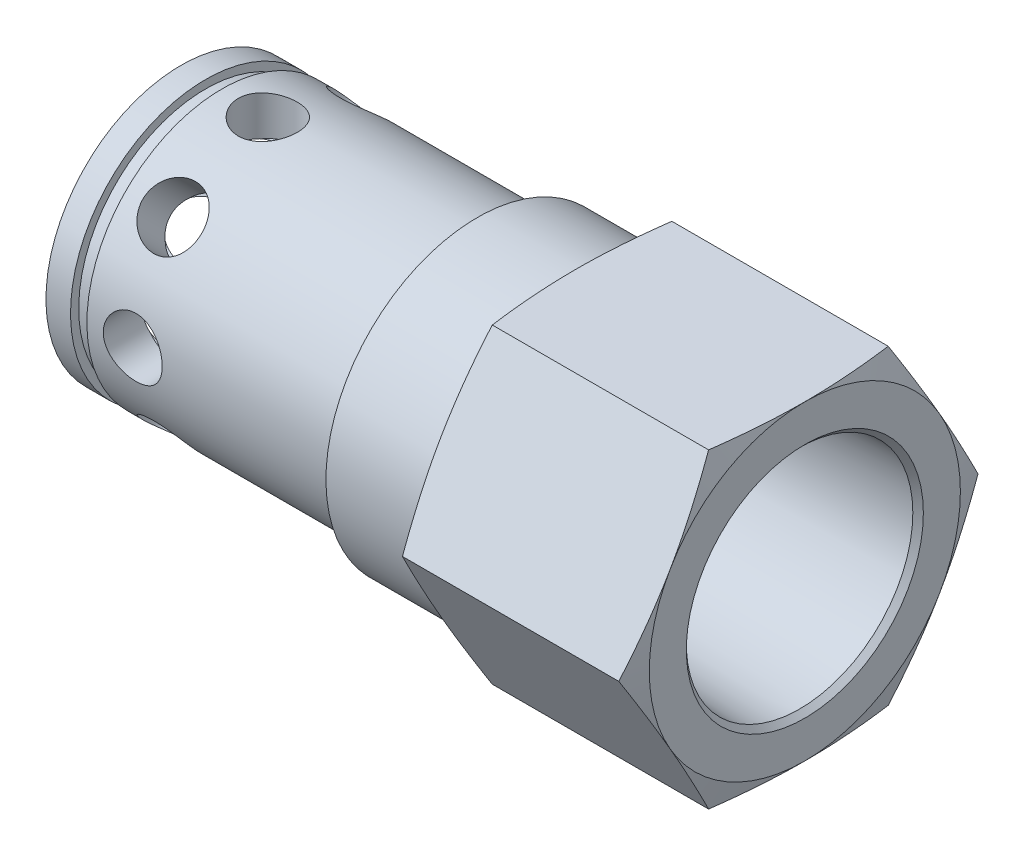
SolidWorks part; units mm, degrees
material "AISI 316 Annealed Stainless Steel Bar (SS)"
ref_plane "Front Plane" through (0, 0, 0) normal (0, 0, 1) x (1, 0, 0)
ref_plane "Top Plane" through (0, 0, 0) normal (0, 1, 0) x (1, 0, 0)
ref_plane "Right Plane" through (0, 0, 0) normal (1, 0, 0) x (0, 0, -1)
sketch "Sketch1" plane through (0, 0, 0) normal (1, 0, 0) x (0, 0, -1)
  line L1 (10.9697, 0) -> (5.4848, 9.5)
  line L2 (5.4848, 9.5) -> (-5.4848, 9.5)
  line L3 (-5.4848, 9.5) -> (-10.9697, 0)
  line L4 (-10.9697, 0) -> (-5.4848, -9.5)
  line L5 (-5.4848, -9.5) -> (5.4848, -9.5)
  line L6 (5.4848, -9.5) -> (10.9697, 0)
  circle A0 centre (0, 0) radius 9.5 construction
  circle A1 centre (0, 0) radius 3
  dimension "D2" = 6
  dimension "D1" = 19
extrude "Boss-Extrude1" add sketch "Sketch1" along normal blind 38.1
sketch "Sketch2" plane through (0, 0, 0) normal (0, 0, 1) x (1, 0, 0)
  line L0 (0, 0) -> (38.1, 0) construction
  line L1 (38.1, 0) -> (0, 0) construction
  line L2 (38.1, 0) -> (38.1, -9.5) construction
  line L3 (38.1, 9.5) -> (0, 9.5) construction
  line L4 (24.1, 9.5) -> (24.1, 9.25)
  line L5 (24.1, 9.25) -> (18.1, 9.25)
  line L6 (18.1, 9.25) -> (18.1, 8.25)
  line L7 (18.1, 8.25) -> (2.5, 8.25)
  line L8 (0, 9.5) -> (0, 0) construction
  line L9 (1.5, 8.25) -> (0, 8.25)
  line L10 (24.1, 9.5) -> (25.0378, 13)
  line L11 (1.5, 8.25) -> (1.5, 7.75)
  line L12 (1.5, 7.75) -> (2.5, 7.75)
  line L13 (2.5, 8.25) -> (2.5, 7.75)
  line L14 (25.0378, 13) -> (0, 13)
  line L15 (0, 13) -> (0, 8.25)
  line L16 (38.1, 9.5) -> (38.1, 13)
  line L17 (38.1, 13) -> (37.1622, 13)
  line L18 (37.1622, 13) -> (38.1, 9.5)
  dimension "D1" = 8.25
  dimension "D2" = 7.75
  dimension "D3" = 1.5
  dimension "D4" = 2.5
  dimension "D5" = 9.25
  dimension "D6" = 24.1
  dimension "D7" = 6
  dimension "D8" = 15
  dimension "D9" = 13
  dimension "D10" = 15
revolve "Cut-Revolve1" cut sketch "Sketch2" angle 360 about L0
sketch "Sketch3" plane through (0, 0, 0) normal (0, 0, 1) x (1, 0, 0)
  line L0 (0, 5.85) -> (9.9, 5.85)
  line L1 (0, 8.25) -> (0, -8.25) construction
  line L2 (9.9, 5.85) -> (10.95, 4.8)
  line L3 (10.95, 4.8) -> (13, 4.8)
  line L4 (13, 4.8) -> (13, 6.25)
  line L5 (13, 6.25) -> (15.5, 6.25)
  line L6 (15.5, 6.25) -> (15.5, 4.8)
  line L7 (15.5, 4.8) -> (21.4, 4.8)
  line L8 (21.4, 4.8) -> (21.4, 0)
  line L9 (0, 0) -> (21.4, 0)
  line L10 (0, 0) -> (0, 5.85)
  dimension "D1" = 9.9
  dimension "D2" = 21.4
  dimension "D3" = 13
  dimension "D4" = 2.5
  dimension "D5" = 4.8
  dimension "D6" = 5.85
  dimension "D7" = 45
  dimension "D8" = 6.25
revolve "Cut-Revolve2" cut sketch "Sketch3" angle 360 about L9
fillet "Fillet1" radius 0.2 2 edges at (15.5, 0, 6.25) (13, 0, 6.25)
hole_wizard "1/4 NPT Tapped Hole1" positions "Sketch5" profile "Sketch4" size "1/4" standard "ANSI Inch"
sketch "Sketch5" plane through (38.1, 0, 0) normal (1, 0, 0) x (0, 0, -1)
  point P0 (0, 0)
sketch "Sketch4" plane through (38.1, 0, 0) normal (0, 1, 0) x (0, 0, -1)
  line L0 (0, 0) -> (0, 14.2)
  line L1 (5.5626, 14.2) -> (0, 14.2)
  line L2 (-5.5626, 14.2) -> (0, 14.2) construction
  line L3 (5.5626, 14.2) -> (5.5626, 12)
  line L4 (5.5626, 12) -> (6.5676, 12)
  line L5 (6.5676, 12) -> (6.9173, 0.3217)
  line L6 (6.9173, 0.3217) -> (7.239, 0)
  line L7 (7.239, 0) -> (0, 0)
  line L8 (0, -6.35) -> (0, 107.95) construction
  line L9 (-6.9173, 0.3217) -> (-7.239, 0) construction
  line L11 (-5.5626, 12) -> (-6.5676, 12) construction
  line L12 (-6.5676, 12) -> (-6.9173, 0.3217) construction
  dimension "Tap Drill Dia." = 11.1252
  dimension "Tap Drill Depth" = 14.2
  dimension "Thread Dia." = 13.8345
  dimension "Thread Angle" = 3.43
  dimension "Thread Depth" = 12
  dimension "C'Sink Dia." = 14.478
  dimension "C'Sink Angle" = 90
  dimension "Drill Angle" = 180
ref_plane "Plane1" through (0, 0, 8.25) normal (0, 0, 1) x (1, 0, 0)
sketch "Sketch12" plane through (0, 0, 0) normal (0, 1, 0) x (1, 0, 0)
  line L0 (5.3, 8.25) -> (5.3, 5.6298)
  line L1 (18.1, 8.25) -> (2.5, 8.25) construction
  line L2 (5.3, 8.25) -> (7.1, 8.25)
  line L3 (7.1, 8.25) -> (7.1, 5.75)
  line L4 (7.1, 5.75) -> (6.9, 5.6298)
  line L5 (6.9, 5.6298) -> (5.3, 5.6298)
  line L6 (0, 8.25) -> (0, -8.25) construction
  dimension "D1" = 1.8
  dimension "D2" = 2.5
  dimension "D3" = 59
  dimension "D4" = 5.3
  dimension "D5" = 1.6
revolve "Cut-Revolve3" cut sketch "Sketch12" angle 360 about L0
pattern_circular "CirPattern1" count 8 over 360 about axis through (0, 0, 0) along (1, 0, 0) of "Cut-Revolve3"
